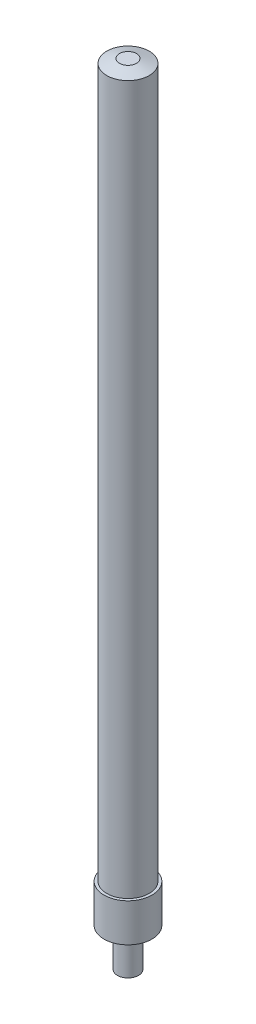
SolidWorks part; units mm, degrees
material "6061 Alloy"
ref_plane "Front Plane" through (0, 0, 0) normal (0, 0, 1) x (1, 0, 0)
ref_plane "Top Plane" through (0, 0, 0) normal (0, 1, 0) x (1, 0, 0)
ref_plane "Right Plane" through (0, 0, 0) normal (1, 0, 0) x (0, 0, -1)
sketch "Sketch1" plane through (0, 0, 0) normal (0, 0, 1) x (1, 0, 0)
  line L0 (0, 0) -> (0, 561.975) construction
  line L1 (0, 561.975) -> (6.35, 561.975)
  line L2 (6.35, 561.975) -> (15.875, 558.8)
  line L3 (15.875, 558.8) -> (15.875, 28.575)
  line L4 (15.875, 28.575) -> (17.9451, 28.575)
  line L5 (17.9451, 28.575) -> (17.9451, 0)
  line L6 (17.9451, 0) -> (7.8867, 0)
  line L7 (7.8867, 0) -> (7.8867, -28.575)
  line L8 (7.8867, -28.575) -> (0, -28.575)
  line L9 (0, -28.575) -> (0, 561.975) construction
  line L10 (0, 561.975) -> (0, -28.575)
  dimension "D1" = 35.8902
  dimension "D2" = 31.75
  dimension "D3" = 15.7734
  dimension "D4" = 28.575
  dimension "D5" = 28.575
  dimension "D6" = 530.225
  dimension "D7" = 3.175
  dimension "D8" = 6.35
revolve "Revolve1" add sketch "Sketch1" angle 360 about L10
